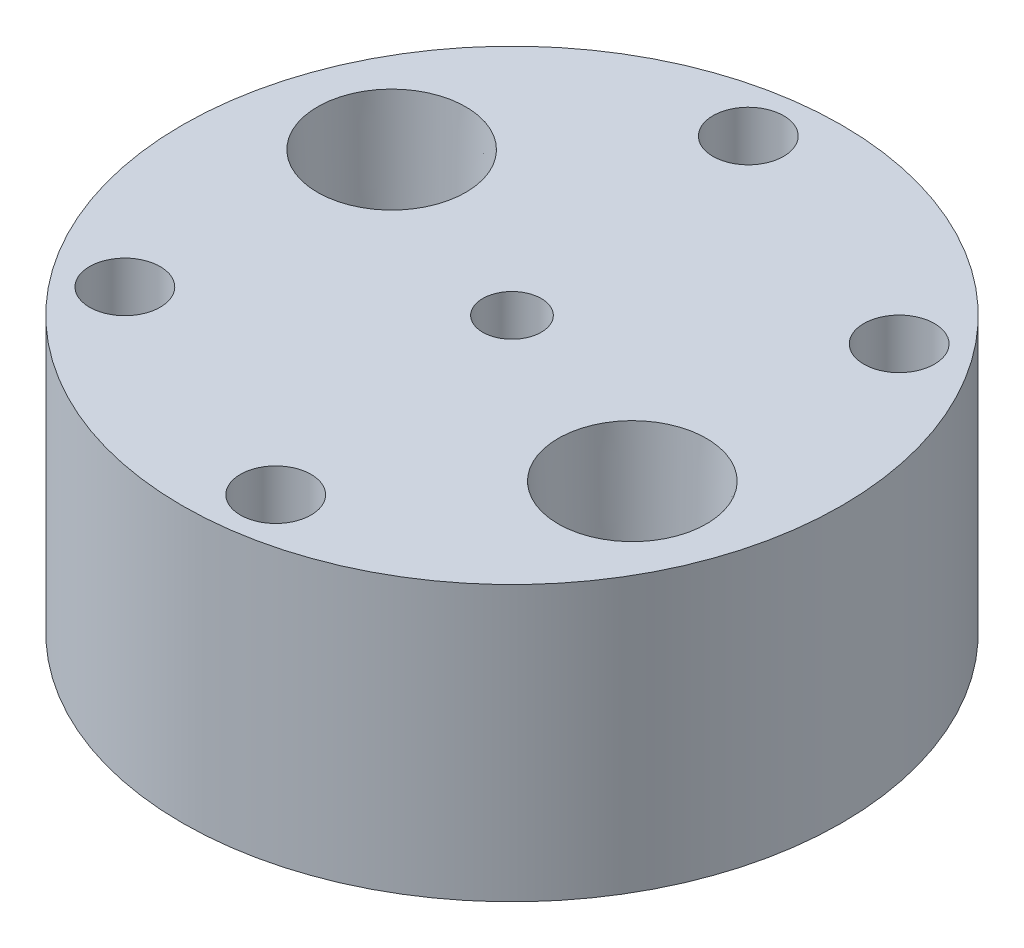
SolidWorks part; units mm, degrees
material "AISI 316 Annealed Stainless Steel Bar (SS)"
ref_plane "Front Plane" through (0, 0, 0) normal (0, 0, 1) x (1, 0, 0)
ref_plane "Top Plane" through (0, 0, 0) normal (0, 1, 0) x (1, 0, 0)
ref_plane "Right Plane" through (0, 0, 0) normal (1, 0, 0) x (0, 0, -1)
sketch "Sketch1" plane through (0, 0, 0) normal (0, 1, 0) x (1, 0, 0)
  circle A0 centre (0, 0) radius 30.48
  dimension "D1" = 60.96
extrude "Boss-Extrude1" add sketch "Sketch1" along normal blind 25.4
sketch "Sketch2" plane through (0, 25.4, 0) normal (0, 1, 0) x (1, 0, 0)
  line L1 (28.9535, 9.525) -> (38.1537, 9.525)
  line L2 (28.9535, 9.525) -> (28.9535, -9.525)
  line L3 (28.9535, -9.525) -> (38.1537, -9.525)
  line L4 (38.1537, 9.525) -> (38.1537, -9.525)
  circle A0 centre (0, 0) radius 30.48 construction
  dimension "D1" = 19.05
extrude "Cut-Extrude1" [suppressed] cut sketch "Sketch2" against normal through all
hole_wizard "1/4-28 Tapped Hole1" positions "Sketch3" profile "Sketch4" tap size "1/4-28" standard "ANSI Inch" end condition through all
sketch "Sketch3" plane through (0, 25.4, 0) normal (0, 1, 0) x (1, 0, 0)
  point P0 (0, 0)
sketch "Sketch4" plane through (0, 25.4, 0) normal (1, 0, 0) x (0, 0, 1)
  line L0 (0, 0) -> (0, 25.4)
  line L1 (0, 25.4) -> (2.7051, 25.4)
  line L2 (2.7051, 25.4) -> (2.7051, 0)
  line L5 (2.7051, 0) -> (0, 0)
  line L11 (0, -6.35) -> (0, 107.95) construction
  dimension "Thru Tap Drill Dia." = 5.4102
  dimension "Thru Tap Drill Depth" = 25.4
cosmetic thread "Hole Thread1" parameters "D2"=6.35
hole_wizard "1/2 NPT Tapped Hole1" [suppressed] positions "Sketch5" profile "Sketch6" size "1/2" standard "ANSI Inch"
sketch "Sketch5" [suppressed] plane through (28.9535, 0, 0) normal (1, 0, 0) x (0, 0, -1)
  line L0 (9.525, 31.75) -> (-9.525, 0) construction
  point P6 (0, 15.875)
sketch "Sketch6" plane through (28.9535, 15.875, 0) normal (0, 1, 0) x (0, 0, -1)
  line L0 (0, 0) -> (0, 20.6045)
  line L1 (8.9281, 15.24) -> (0, 20.6045)
  line L2 (-8.9281, 15.24) -> (0, 20.6045) construction
  line L3 (8.9281, 15.24) -> (8.9281, 13.462)
  line L4 (8.9281, 13.462) -> (10.2617, 13.462)
  line L5 (10.2617, 13.462) -> (10.6647, 0)
  line L6 (-10.2617, 13.462) -> (-10.6647, 0) construction
  line L7 (10.6647, 0) -> (0, 0)
  line L8 (0, -6.35) -> (0, 107.95) construction
  line L11 (-8.9281, 13.462) -> (-10.2617, 13.462) construction
  dimension "Tap Drill Dia." = 17.8562
  dimension "Tap Drill Depth" = 15.24
  dimension "Thread Dia." = 21.3295
  dimension "Thread Angle" = 3.43
  dimension "Thread Depth" = 13.462
  dimension "Drill Angle" = 118
sketch "Sketch7" plane through (0, 0, 0) normal (0, -1, 0) x (1, 0, 0)
  circle A0 centre (0, 0) radius 11.43
  dimension "D1" = 22.86
extrude "Cut-Extrude2" cut sketch "Sketch7" against normal blind 12.7
hole_wizard "1/4 Clearance Hole1" positions "Sketch8" profile "Sketch9" hole size "1/4" standard "ANSI Inch" end condition through all
sketch "Sketch8" plane through (0, 25.4, 0) normal (0, 1, 0) x (1, 0, 0)
  point P3 (20.1755, 15.6153)
  point P6 (3.4355, -25.2801)
  point P11 (-3.4355, 25.2801)
  point P14 (-20.1755, -15.6153)
sketch "Sketch9" plane through (20.1755, 25.4, -15.6153) normal (1, 0, 0) x (0, 0, 1)
  line L0 (0, 0) -> (0, 25.4)
  line L1 (0, 25.4) -> (3.2639, 25.4)
  line L2 (3.2639, 25.4) -> (3.2639, 0)
  line L5 (3.2639, 0) -> (0, 0)
  line L11 (0, -6.35) -> (0, 107.95) construction
  dimension "Thru Hole Dia." = 6.5278
  dimension "Thru Hole Depth" = 25.4
sketch "nipple-layout" plane through (0, 25.4, 0) normal (0, 1, 0) x (1, 0, 0)
  line L0 (-18.8349, 7.7098) -> (18.8349, -7.7098) construction
  line L1 (-20.1755, -15.6153) -> (3.4355, -25.2801) construction
  circle A0 centre (0, 0) radius 7.9375 construction
  circle A1 centre (-18.8349, 7.7098) radius 11.9062 construction
  point P5 (0, 0)
  dimension "D1" = 15.875
  dimension "D2" = 23.8125
  dimension "D3" = 0.508
hole_wizard "1/4 NPT Tapped Hole1" positions "Sketch11" profile "Sketch12" size "1/4" standard "ANSI Inch" end condition through all
sketch "Sketch11" plane through (0, 25.4, 0) normal (0, 1, 0) x (1, 0, 0)
  point P0 (-18.8349, 7.7098)
  point P3 (18.8349, -7.7098)
sketch "Sketch12" plane through (-18.8349, 25.4, -7.7098) normal (1, 0, 0) x (0, 0, 1)
  line L0 (0, 0) -> (0, 25.4)
  line L1 (0, 25.4) -> (5.5626, 25.4)
  line L2 (-6.558, 9.906) -> (-6.8546, 0) construction
  line L3 (5.5626, 25.4) -> (5.5626, 9.906)
  line L4 (5.5626, 9.906) -> (6.558, 9.906)
  line L5 (6.558, 9.906) -> (6.8546, 0)
  line L7 (6.8546, 0) -> (0, 0)
  line L8 (0, -6.35) -> (0, 107.95) construction
  line L11 (-5.5626, 9.906) -> (-6.558, 9.906) construction
  dimension "Thru Tap Drill Dia." = 11.1252
  dimension "Thru Tap Drill Depth" = 25.4
  dimension "Thread Dia." = 13.7092
  dimension "Thread Angle" = 3.43
  dimension "Thread Depth" = 9.906
sketch "Sketch13" plane through (0, 0, 0) normal (0, -1, 0) x (1, 0, 0)
  line L0 (-7.1958, 8.8806) -> (-22.3368, -3.3879)
  line L1 (-18.3012, -13.2468) -> (1.0965, -11.3773)
  line L2 (22.3368, 3.3879) -> (7.1958, -8.8806)
  line L3 (18.3012, 13.2468) -> (-1.0965, 11.3773)
  circle A0 centre (-18.8349, -7.7098) radius 5.5626 construction
  circle A1 centre (18.8349, 7.7098) radius 5.5626 construction
  circle A2 centre (0, 0) radius 11.43 construction
  arc A3 (-22.3368, -3.3879) -> (-18.3012, -13.2468) centre (-18.8349, -7.7098) ccw
  arc A4 (22.3368, 3.3879) -> (18.3012, 13.2468) centre (18.8349, 7.7098) ccw
  arc A5 (-1.0965, 11.3773) -> (-7.1958, 8.8806) centre (0, 0) ccw
  arc A6 (1.0965, -11.3773) -> (7.1958, -8.8806) centre (0, 0) ccw
extrude "Cut-Extrude3" cut sketch "Sketch13" against normal blind 12.7
sketch "Sketch16" plane through (0, 0, 0) normal (0, -1, 0) x (1, 0, 0)
  line L0 (18.155, 14.7638) -> (-1.2427, 12.8943)
  line L1 (-8.1553, 10.0647) -> (-23.2963, -2.2039)
  line L2 (-18.155, -14.7638) -> (1.2427, -12.8943)
  line L3 (8.1553, -10.0647) -> (23.2963, 2.2039)
  line L4 (18.3012, 13.2468) -> (-1.0965, 11.3773)
  line L5 (7.1958, -8.8806) -> (22.3368, 3.3879)
  line L6 (-18.3012, -13.2468) -> (1.0965, -11.3773)
  line L7 (-7.1958, 8.8806) -> (-22.3368, -3.3879)
  line L8 (18.3012, 13.2468) -> (-1.0965, 11.3773) construction
  line L9 (7.1958, -8.8806) -> (22.3368, 3.3879) construction
  line L10 (-18.3012, -13.2468) -> (1.0965, -11.3773) construction
  line L11 (-7.1958, 8.8806) -> (-22.3368, -3.3879) construction
  line L12 (18.0088, 16.2807) -> (-1.3889, 14.4112)
  line L13 (-9.1147, 11.2488) -> (-24.2557, -1.0198)
  line L14 (-18.0088, -16.2807) -> (1.3889, -14.4112)
  line L15 (9.1147, -11.2488) -> (24.2557, 1.0198)
  arc A0 (-1.2427, 12.8943) -> (-8.1553, 10.0647) centre (0, 0) ccw
  arc A1 (-23.2963, -2.2039) -> (-18.155, -14.7638) centre (-18.8349, -7.7098) ccw
  arc A2 (1.2427, -12.8943) -> (8.1553, -10.0647) centre (0, 0) ccw
  arc A3 (23.2963, 2.2039) -> (18.155, 14.7638) centre (18.8349, 7.7098) ccw
  arc A4 (-1.0965, 11.3773) -> (-7.1958, 8.8806) centre (0, 0) ccw
  arc A5 (22.3368, 3.3879) -> (18.3012, 13.2468) centre (18.8349, 7.7098) ccw
  arc A6 (1.0965, -11.3773) -> (7.1958, -8.8806) centre (0, 0) ccw
  arc A7 (-22.3368, -3.3879) -> (-18.3012, -13.2468) centre (-18.8349, -7.7098) ccw
  arc A8 (-1.0965, 11.3773) -> (-7.1958, 8.8806) centre (0, 0) ccw construction
  arc A9 (22.3368, 3.3879) -> (18.3012, 13.2468) centre (18.8349, 7.7098) ccw construction
  arc A10 (1.0965, -11.3773) -> (7.1958, -8.8806) centre (0, 0) ccw construction
  arc A11 (-22.3368, -3.3879) -> (-18.3012, -13.2468) centre (-18.8349, -7.7098) ccw construction
  arc A12 (-1.3889, 14.4112) -> (-9.1147, 11.2488) centre (0, 0) ccw
  arc A13 (-24.2557, -1.0198) -> (-18.0088, -16.2807) centre (-18.8349, -7.7098) ccw
  arc A14 (1.3889, -14.4112) -> (9.1147, -11.2488) centre (0, 0) ccw
  arc A15 (24.2557, 1.0198) -> (18.0088, 16.2807) centre (18.8349, 7.7098) ccw
  dimension "D1" = 0
  dimension "D2" = 1.524
  dimension "D3" = 1.524
extrude "gasket slot" cut sketch "Sketch16" against normal blind 1.016
